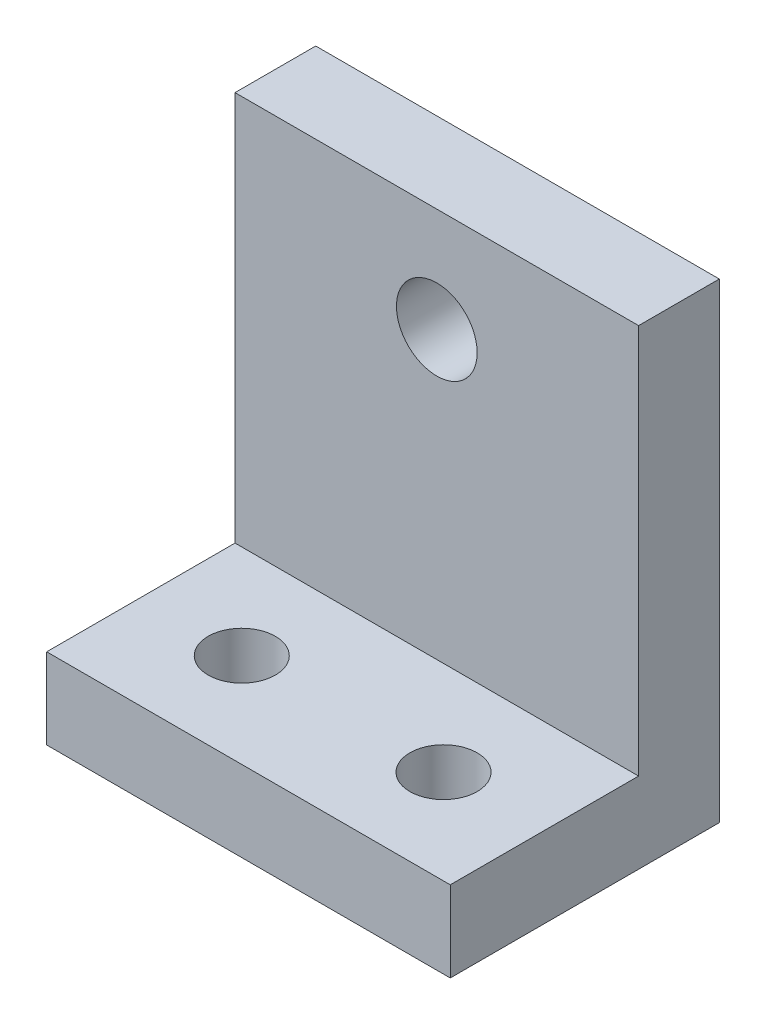
SolidWorks part; units mm, degrees
ref_plane "Alzado" through (0, 0, 0) normal (0, 0, 1) x (1, 0, 0)
ref_plane "Planta" through (0, 0, 0) normal (0, 1, 0) x (1, 0, 0)
ref_plane "Vista lateral" through (0, 0, 0) normal (1, 0, 0) x (0, 0, -1)
sketch "Croquis1" plane through (0, 0, 0) normal (0, 1, 0) x (1, 0, 0)
  line L1 (-15, -10) -> (15, -10)
  line L2 (-15, -10) -> (-15, 10)
  line L3 (-15, 10) -> (15, 10)
  line L4 (15, -10) -> (15, 10)
  line L5 (-15, -10) -> (15, 10) construction
  line L6 (-15, 10) -> (15, -10) construction
  point P0 (0, 0)
  dimension "D1" = 30
  dimension "D2" = 20
extrude "Saliente-Extruir1" add sketch "Croquis1" along normal blind 6
sketch "Croquis2" plane through (0, 0, -10) normal (0, 0, -1) x (-1, 0, 0)
  line L1 (-15, 0) -> (15, 0)
  line L2 (-15, 0) -> (-15, 35)
  line L3 (-15, 35) -> (15, 35)
  line L4 (15, 0) -> (15, 35)
  line L5 (15, 6) -> (15, 0) construction
  dimension "D1" = 0
  dimension "D2" = 35
extrude "Saliente-Extruir2" add sketch "Croquis2" against normal blind 6
sketch "Croquis3" plane through (0, 0, -4) normal (0, 0, 1) x (1, 0, 0)
  line L0 (-15, 0) -> (15, 0) construction
  circle A0 centre (0, 27.25) radius 3
  dimension "D2" = 6
  dimension "D1" = 27.25
extrude "Cortar-Extruir1" cut sketch "Croquis3" against normal blind 6
sketch "Croquis4" plane through (0, 6, 0) normal (0, 1, 0) x (1, 0, 0)
  line L0 (-15, -10) -> (15, -10) construction
  line L1 (-15, 4) -> (-15, -10) construction
  line L2 (15, -10) -> (15, 4) construction
  circle A0 centre (-7.5, -3) radius 2.5
  circle A1 centre (7.5, -3) radius 2.5
  point P6 (0, 0)
  dimension "D4" = 5
  dimension "D1" = 7
  dimension "D2" = 7.5
  dimension "D3" = 7.5
extrude "Cortar-Extruir2" cut sketch "Croquis4" against normal blind 6
